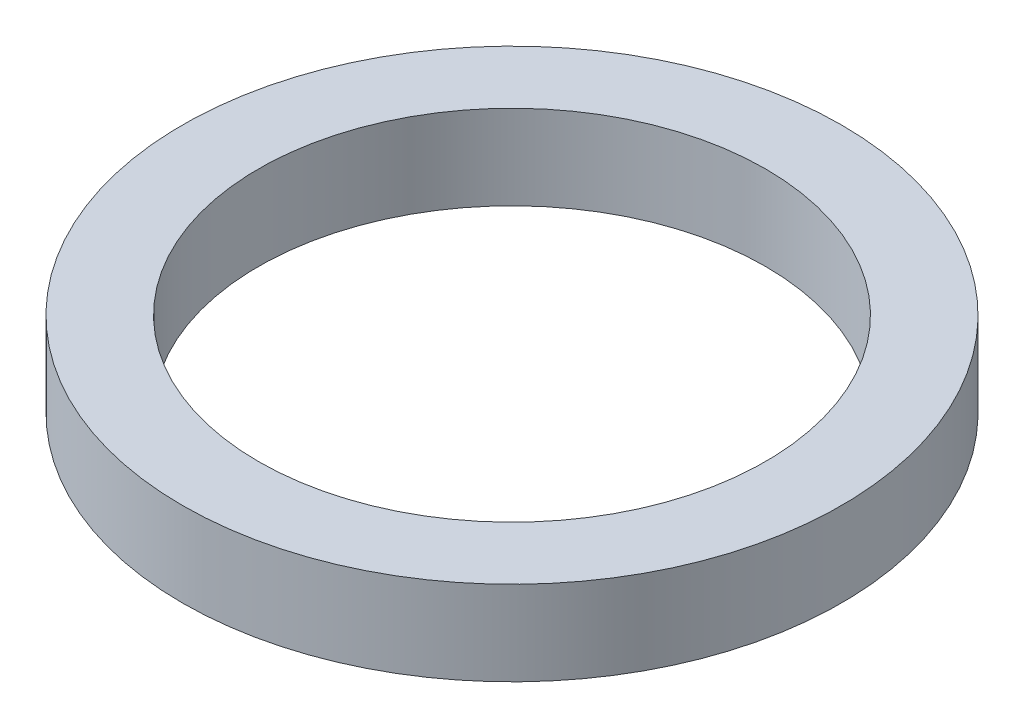
SolidWorks part; units mm, degrees
ref_plane "Front Plane" through (0, 0, 0) normal (0, 0, 1) x (1, 0, 0)
ref_plane "Top Plane" through (0, 0, 0) normal (0, 1, 0) x (1, 0, 0)
ref_plane "Right Plane" through (0, 0, 0) normal (1, 0, 0) x (0, 0, -1)
sketch "Sketch1" plane through (0, 0, 0) normal (0, 1, 0) x (1, 0, 0)
  circle A0 centre (0, 0) radius 30
  circle A1 centre (0, 0) radius 39
  dimension "D1" = 60
  dimension "D2" = 78
extrude "Boss-Extrude1" add sketch "Sketch1" along normal mid plane 10
equation "\"module\" = 0.5"
equation "\"pressure_angle\" = 20.0"
equation "\"h_a\" = 0.5"
equation "\"h_f\" = 0.625"
equation "\"clr_tip_root\" = 0.125"
equation "\"bearing_ID\" = 60"
equation "\"bearing_OD\" = 78"
equation "\"bearing_height\" = 10"
equation "\"clearance_planet\" = 1.5"
equation "\"case_dist\" = 6.5"
equation "\"Motor_case_OD_max\" = 111.3"
equation "\"case_mounting_PCD\" = 103.8"
equation "\"bearing mount thickness\" = 8"
equation "\"case_mounting_hole_dia\" = 3"
equation "\"output_mounting_PCD\" = 86"
equation "\"output_mounting_hole_dia\" = 4"
equation "\"clearance_case_mount_holes_shell_thickness\" = 1"
equation "\"motor_case_OD_base\" = 101.8"
equation "\"sec_carrier_thickness\" = 5"
equation "\"sun_coupler_hub_thickness\" = 4"
equation "\"clearance_sun_coupler_sec_carrier\" = 1.5"
equation "\"clearance_motor_and_case\" = 5"
equation "\"motor_OD\" = 86.8"
equation "\"Motor_case_thickness\" = 2.5"
equation "\"Motor_case_ID\" = 96.8"
equation "\"case_mounting_hole_shift\" = 1.0"
equation "\"output_mounting_nut_wrench_size\" = 7"
equation "\"output_mounting_nut_thickness\" = 3.2"
equation "\"case_mounting_hole_allen_socket_dia\" = 5.5"
equation "\"output_mounting_nut_depth\" = 3"
equation "\"case_mounting_bolt_depth\" = 4.5"
equation "\"Ns\" = 56"
equation "\"ring_radial_thickness\" = 5"
equation "\"ring_to_chamfer_clearance\" = 1.5"
equation "\"Motor_case_OD_base_to_chamfer\" = 5"
equation "\"pattern_offset_from_motor_case_OD_base\" = 3"
equation "\"pattern_bulge_dia\" = 3"
equation "\"pattern_num_bulge\" = 18"
equation "\"pattern_depth\" = 2"
equation "\"motor_height\" = 26.5"
equation "\"case_mounting_wrench_size\" = 5.5"
equation "\"case_mounting_nut_clearance\" = 2"
equation "\"base_plate_thickness\" = 4"
equation "\"case_mounting_nut_thickness\" = 2.4"
equation "\"case_mounting_surface_height\" = 4"
equation "\"motor_mount_hole_PCD\" = 32"
equation "\"motor_mount_hole_dia\" = 4"
equation "\"motor_mount_hole_num\" = 4"
equation "\"central_hole_offset_from_motor_mount_PCD\" = 5"
equation "\"wire_slot_dist_from_center\" = 38"
equation "\"wire_slot_length\" = 10"
equation "\"wire_slot_radius\" = 2.5"
equation "\"driver_upper_holes_dist_from_center\" = 29"
equation "\"driver_lower_holes_dist_from_center\" = 13"
equation "\"driver_side_holes_dist_from_center\" = 22.5"
equation "\"driver_mount_holes_dia\" = 3"
equation "\"driver_mount_inserts_OD\" = 4.8"
equation "\"driver_mount_thickness\" = 1.5"
equation "\"driver_mount_height\" = 6"
equation "\"air_flow_hole_offset\" = 3"
equation "\"num_planet\" = 4"
equation "\"planet_pin_bolt_dia\" = 5"
equation "\"planet_pin_socket_head_dia\" = 8.5"
equation "\"carrier_PCD\" = 52.0"
equation "\"planet_shaft_dia\" = 8"
equation "\"planet_shaft_step_offset\" = 1"
equation "\"carrier_trapezoidal_support_sun_offset\" = 5"
equation "\"carrier_trapezoidal_support_hole_PCD_offset_bearing_ID\" = 4"
equation "\"carrier_trapezoidal_support_hole_dia\" = 3"
equation "\"carrier_trapezoidal_support_hole_socket_head_dia\" = 5.5"
equation "\"carrier_bearing_step_width\" = 1.5"
equation "\"standard_clearance_1_5mm\" = 1.5"
equation "\"standard_fillet_1_5mm\" = 1.5"
equation "\"sun_shaft_bearing_OD\" = 16"
equation "\"sun_shaft_bearing_width\" = 5"
equation "\"standard_bearing_insertion_chamfer\" = 0.5"
equation "\"D1@Sketch1\"=\"bearing_ID\""
equation "\"D2@Sketch1\"=\"bearing_OD\""
equation "\"D1@Boss-Extrude1\"=\"bearing_height\""
equation "\"carrier_trapezoidal_support_hole_wrench_size\" = 5.5"
equation "\"planet_pin_bolt_wrench_size\" = 8"
equation "\"Np_b\" = 48"
equation "\"pressure angle\" = 20.0"
equation "\"h_b\" = 0.625"
equation "\"dp_s\" = 28.0"
equation "\"db_s\" = 26.311393382005434"
equation "\"fw_s_calc\" = 2.7970255760332914"
equation "\"alpha_s\" = 0.8539582918412485"
equation "\"beta_s\" = 1.5063691306032174"
equation "\"dp_p_b\" = 24.0"
equation "\"db_p_b\" = 22.552622898861802"
equation "\"fw_p_s\" = 15.90536252346366"
equation "\"alpha_p_b\" = 0.8539582918412414"
equation "\"beta_p_b\" = 2.042083416317517"
equation "\"planet_bearing_OD\" = 12"
equation "\"planet_bearing_width\" = 3.5"
equation "\"planet_bore\" = 10"
equation "\"motor_output_hole_PCD\" = 23"
equation "\"motor_output_hole_dia\" = 4"
equation "\"motor_output_hole_num\" = 4"
equation "\"sun_shaft_bearing_ID\" = 8"
equation "\"sun_hub_dia\" = 30.0"
equation "\"sun_central_bolt_dia\" = 5"
equation "\"sun_central_bolt_socket_head_dia\" = 8.5"
equation "\"fw_s_used\" = 33.32338113475014"
equation "\"motor_output_hole_CSK_OD\" = 8"
equation "\"motor_output_hole_CSK_head_height\" = 2.0"
equation "\"bearing_retainer_thickness\" = 2"
equation "\"Np_s\" = 28"
equation "\"fw_p_b\" = 9.918018611286483"
equation "\"dp_p_s\" = 14.0"
equation "\"db_p_s\" = 13.155696691002717"
equation "\"alpha_p_s\" = 0.8539582918412485"
equation "\"beta_p_s\" = 4.720654844888932"
equation "\"Nr_b\" = 152"
equation "\"dp_r_b\" = 76.0"
equation "\"db_r_b\" = 71.41663917972905"
equation "\"fw_r_b\" = 9.918018611286483"
equation "\"alpha_r_b\" = 0.8539582918412236"
equation "\"beta_r_b\" = 2.8921271099982366"
equation "\"ring_OD_b\" = 86.0"
equation "\"Fillet10\"= IIF ( \"ring_OD_b\" > ( \"bearing_OD\" + 2 * \"bearing mount thickness\" ) , \"suppressed\" , \"unsuppressed\" )"
equation "\"Fillet11\"= IIF ( \"ring_OD_b\" < ( \"bearing_OD\" + 2 * \"bearing mount thickness\" ) , \"suppressed\" , \"unsuppressed\" )"
equation "\"Nr_s\" = 132"
equation "\"clr_tip_root_s\" = 0.125"
equation "\"dp_r_s\" = 66.0"
equation "\"db_r_s\" = 62.01971297186996"
equation "\"fw_r_s\" = 14.40536252346366"
equation "\"alpha_r_s\" = 0.8539582918412449"
equation "\"beta_r_s\" = 3.071552947318853"
equation "\"small_ring_case_thickness\" = 4"
equation "\"carrier_thickness\" = 4"
equation "\"small_ring_output_wall_thickness\" = 5"
equation "\"small_ring_output_wall_to_bearing_shaft_attachement_hole_dia\" = 4"
equation "\"small_ring_output_wall_to_bearing_shaft_attachement_hole_depth\" = 6.5"
equation "\"small_ring_output_wall_to_bearing_shaft_attachement_nut_wrench\" = 7"
equation "\"small_ring_output_wall_to_bearing_shaft_attachement_nut_thickness\" = 3.2"
equation "\"small_ring_output_wall_to_bearing_shaft_attachement_hole_pcd\" = 12"
equation "\"small_ring_output_wall_to_bearing_shaft_attachement_hole_num\" = 3"
equation "\"small_ring_output_wall_to_bearing_shaft_attachement_hole_CSK_OD\" = 8"
equation "\"small_ring_output_wall_to_bearing_shaft_attachement_hole_CSK_head_height\" = 2.0"
equation "\"carrier_small_ring_inner_bearing_ID\" = 20"
equation "\"carrier_small_ring_inner_bearing_OD\" = 32"
equation "\"carrier_small_ring_inner_bearing_height\" = 7"
equation "\"carrier_small_ring_inner_bearing_flap\" = 2"
equation "\"gear_casing_big_ring_to_bearing_dist\" = 24.90536252346366"
equation "\"gear_casing_thickness\" = 4"
